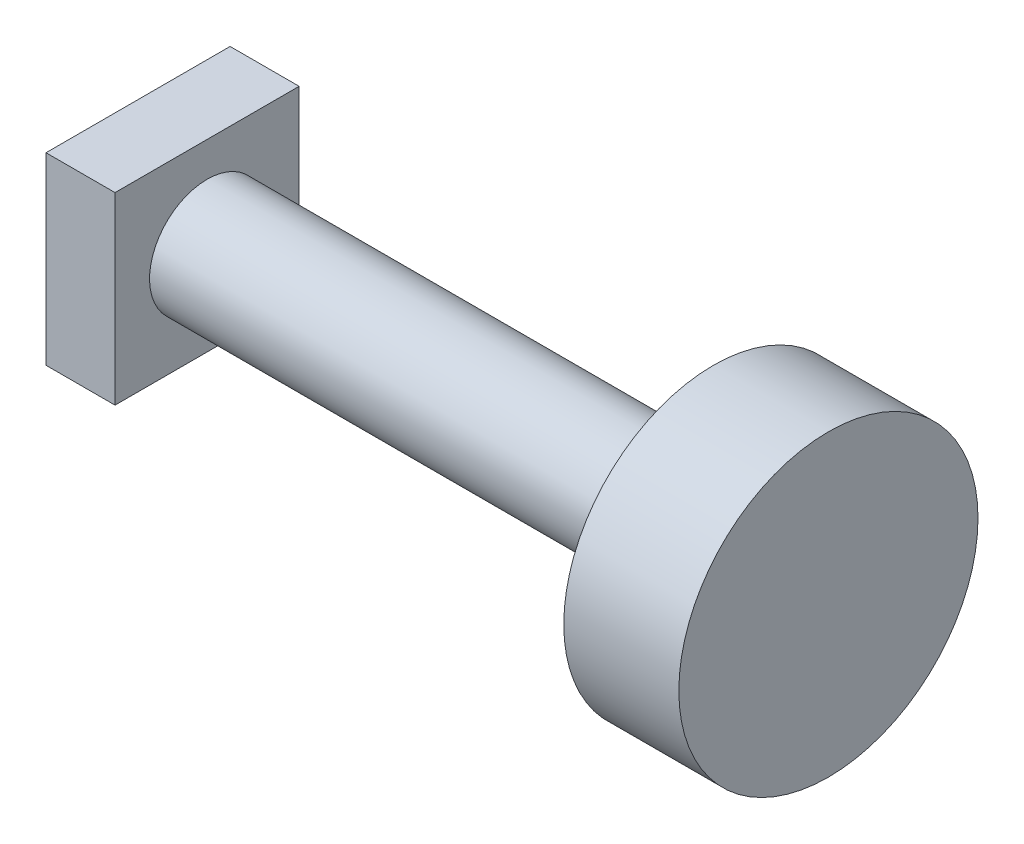
SolidWorks part; units mm, degrees
ref_plane "前基準面" through (0, 0, 0) normal (0, 0, 1) x (1, 0, 0)
ref_plane "上基準面" through (0, 0, 0) normal (0, 1, 0) x (1, 0, 0)
ref_plane "右基準面" through (0, 0, 0) normal (1, 0, 0) x (0, 0, -1)
sketch "草圖1" plane through (0, 0, 0) normal (0, 0, 1) x (1, 0, 0)
  line L0 (0, 0) -> (0, 2.5)
  line L1 (0, 2.5) -> (25, 2.5)
  line L2 (25, 2.5) -> (25, 6.5)
  line L3 (25, 6.5) -> (30, 6.5)
  line L4 (30, 6.5) -> (30, 0)
  line L5 (30, 0) -> (0, 0)
  dimension "D1" = 30
  dimension "D2" = 5
  dimension "D3" = 6.5
  dimension "D4" = 2.5
revolve "旋轉1" add sketch "草圖1" angle 360 about L5
sketch "草圖3" plane through (0, 0, 0) normal (-1, 0, 0) x (0, 0, 1)
  line L1 (-4, -4) -> (4, -4)
  line L2 (-4, -4) -> (-4, 4)
  line L3 (-4, 4) -> (4, 4)
  line L4 (4, -4) -> (4, 4)
  line L5 (-4, -4) -> (4, 4) construction
  line L6 (-4, 4) -> (4, -4) construction
  point P0 (0, 0)
  dimension "D1" = 8
extrude "填料-伸長1" add sketch "草圖3" against normal blind 3
